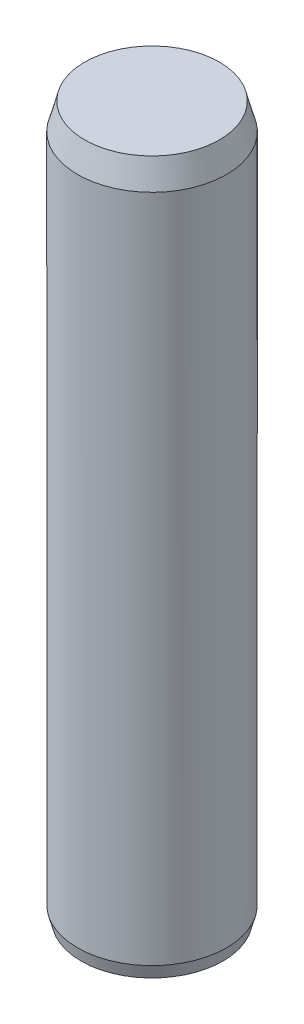
SolidWorks part; units mm, degrees
material "1.7131 (16MnCr5)"
ref_plane "Front Plane" through (0, 0, 0) normal (0, 0, 1) x (1, 0, 0)
ref_plane "Top Plane" through (0, 0, 0) normal (0, 1, 0) x (1, 0, 0)
ref_plane "Right Plane" through (0, 0, 0) normal (1, 0, 0) x (0, 0, -1)
sketch "Sketch1" plane through (0, 0, 0) normal (0, 1, 0) x (1, 0, 0)
  circle A0 centre (0, 0) radius 21
  dimension "D1" = 42
extrude "Boss-Extrude1" add sketch "Sketch1" along normal blind 200
chamfer "Chamfer1" distance 2 angle 75 1 edges at (0, 200, 21)
chamfer "Chamfer2" distance 1 angle 75 1 edges at (0, 0, 21)
